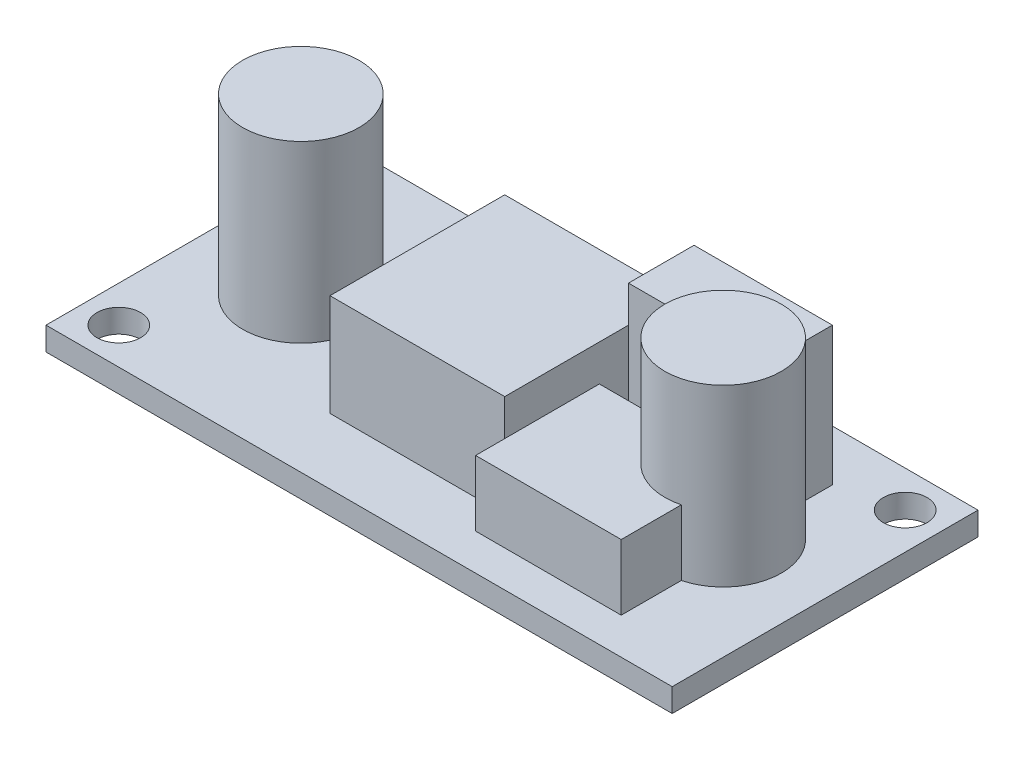
SolidWorks part; units mm, degrees
ref_plane "Front Plane" through (0, 0, 0) normal (0, 0, 1) x (1, 0, 0)
ref_plane "Top Plane" through (0, 0, 0) normal (0, 1, 0) x (1, 0, 0)
ref_plane "Right Plane" through (0, 0, 0) normal (1, 0, 0) x (0, 0, -1)
other "Configuration Table"
sketch "Sketch1" plane through (0, 0, 0) normal (0, 1, 0) x (1, 0, 0)
  line L1 (0, 0) -> (43, 0)
  line L2 (0, 0) -> (0, 21)
  line L3 (0, 21) -> (43, 21)
  line L4 (43, 0) -> (43, 21)
extrude "PCB" add sketch "Sketch1" along normal blind 1.6
sketch "Sketch2" plane through (0, 0, 0) normal (0, 1, 0) x (1, 0, 0)
  circle A0 centre (2.5, 2.5) radius 1.5
extrude "Mount_hole_1" cut sketch "Sketch2" against normal through all and the other way through all
sketch "Sketch3" plane through (0, 0, 0) normal (0, 1, 0) x (1, 0, 0)
  circle A0 centre (40.5, 18.5) radius 1.5
extrude "Mount_hole_2" cut sketch "Sketch3" against normal through all and the other way through all
sketch "Sketch4" plane through (0, 0, 0) normal (0, 1, 0) x (1, 0, 0)
  line L1 (15, 4.5) -> (27, 4.5)
  line L2 (15, 4.5) -> (15, 16.5)
  line L3 (15, 16.5) -> (27, 16.5)
  line L4 (27, 4.5) -> (27, 16.5)
extrude "Inductor" add sketch "Sketch4" along normal blind 7 from offset 1.6
sketch "Sketch5" plane through (0, 0, 0) normal (0, 1, 0) x (1, 0, 0)
  circle A0 centre (7, 10.5) radius 4
extrude "Cap_in" add sketch "Sketch5" along normal blind 12 from offset 1.6
sketch "Sketch6" plane through (0, 0, 0) normal (0, 1, 0) x (1, 0, 0)
  circle A0 centre (36, 10.5) radius 4
extrude "Cap_out" add sketch "Sketch6" along normal blind 12 from offset 1.6
sketch "Sketch7" plane through (0, 0, 0) normal (0, 1, 0) x (1, 0, 0)
  line L1 (27, 13) -> (36.5, 13)
  line L2 (27, 13) -> (27, 17.5)
  line L3 (27, 17.5) -> (36.5, 17.5)
  line L4 (36.5, 13) -> (36.5, 17.5)
extrude "Trim_pot" add sketch "Sketch7" along normal blind 9.5 from offset 1.6
sketch "Sketch8" plane through (0, 0, 0) normal (0, 1, 0) x (1, 0, 0)
  line L1 (27, 2.5) -> (37, 2.5)
  line L2 (27, 2.5) -> (27, 11)
  line L3 (27, 11) -> (37, 11)
  line L4 (37, 2.5) -> (37, 11)
extrude "LM2596S" add sketch "Sketch8" along normal blind 4.5 from offset 1.6
